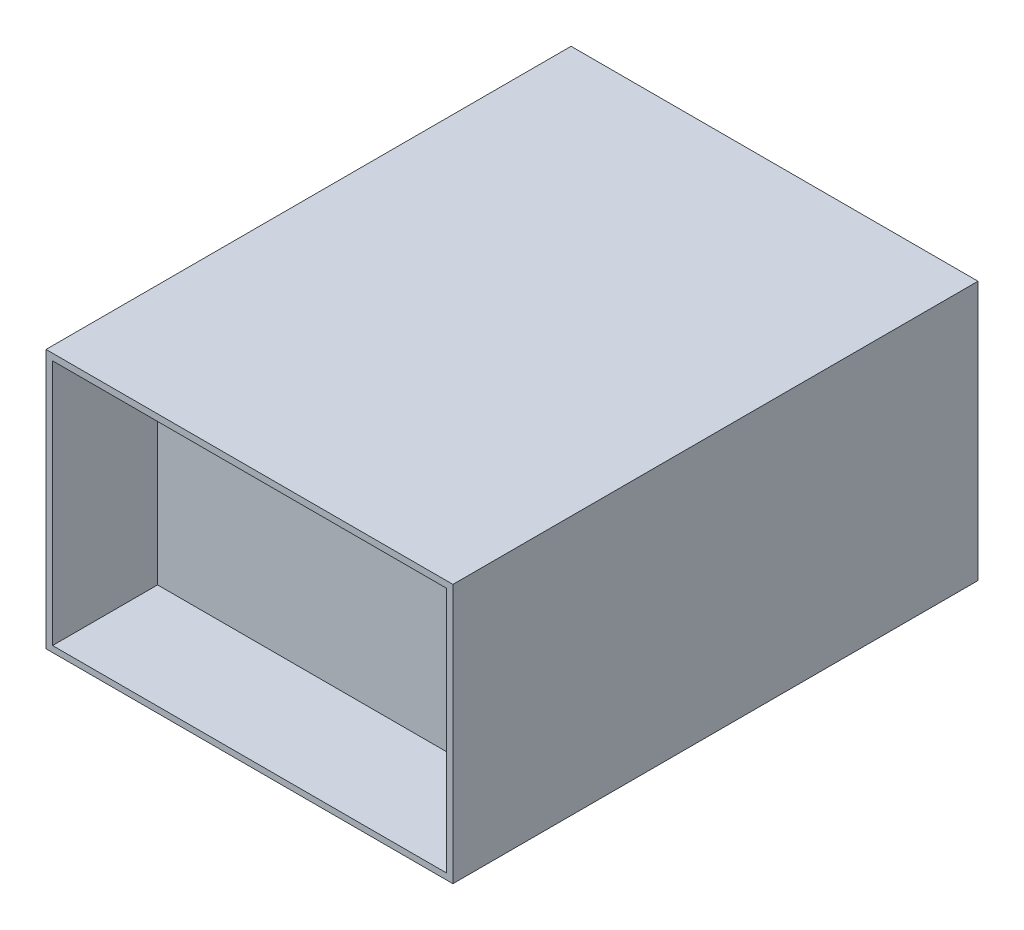
SolidWorks part; units mm, degrees
ref_plane "Front Plane" through (0, 0, 0) normal (0, 0, 1) x (1, 0, 0)
ref_plane "Top Plane" through (0, 0, 0) normal (0, 1, 0) x (1, 0, 0)
ref_plane "Right Plane" through (0, 0, 0) normal (1, 0, 0) x (0, 0, -1)
sketch "Sketch1" plane through (0, 0, 0) normal (0, 0, 1) x (1, 0, 0)
  line L1 (3100, -1975) -> (-3100, -1975)
  line L2 (3100, -1975) -> (3100, 1975)
  line L3 (3100, 1975) -> (-3100, 1975)
  line L4 (-3100, -1975) -> (-3100, 1975)
  line L5 (3100, -1975) -> (-3100, 1975) construction
  line L6 (3100, 1975) -> (-3100, -1975) construction
  point P0 (0, 0)
  dimension "D1" = 6200
  dimension "D2" = 3950
extrude "Boss-Extrude1" add sketch "Sketch1" along normal blind 8000
sketch "Sketch2" plane through (0, 0, 0) normal (0, 0, 1) x (1, 0, 0)
  line L0 (-3100, -1975) -> (3100, -1975) construction
  line L2 (-2500, -1875) -> (2500, -1875)
  line L3 (-2500, -1875) -> (-2500, 1625)
  line L4 (-2500, 1625) -> (2500, 1625)
  line L5 (2500, -1875) -> (2500, 1625)
  line L6 (-3100, 1975) -> (-3100, -1975) construction
  dimension "D1" = 100
  dimension "D2" = 600
  dimension "D3" = 3500
  dimension "D4" = 5000
extrude "Cut-Extrude3" cut sketch "Sketch2" along normal blind 6200
sketch "Sketch4" plane through (0, 0, 0) normal (0, 0, 1) x (1, 0, 0)
  line L0 (2500, -1875) -> (2500, 1625) construction
  line L1 (3000, -1875) -> (2550, -1875)
  line L2 (3000, -1875) -> (3000, 1875)
  line L3 (3000, 1875) -> (2550, 1875)
  line L4 (2550, -1875) -> (2550, 1875)
  line L5 (3100, 1975) -> (-3100, 1975) construction
  line L7 (-3100, 1975) -> (-3100, -1975) construction
  line L8 (-2550, -1882.0855) -> (-3000, -1882.0855)
  line L9 (-2550, -1882.0855) -> (-2550, 1867.9145)
  line L10 (-2550, 1867.9145) -> (-3000, 1867.9145)
  line L11 (-3000, -1882.0855) -> (-3000, 1867.9145)
  point P14 (-2550, 1867.9145)
  dimension "D1" = 450
  dimension "D2" = 50
  dimension "D3" = 3750
  dimension "D4" = 100
  dimension "D5" = 3750
  dimension "D6" = 450
  dimension "D7" = 100
extrude "Cut-Extrude5" cut sketch "Sketch4" along normal blind 6200 contours L10 L11 L8 L9 | L3 L4 L1 L2
sketch "Sketch5" plane through (0, 0, 0) normal (0, 0, -1) x (-1, 0, 0)
  line L0 (-2500, 1625) -> (2500, 1625) construction
  line L1 (-2500, 1875) -> (2500, 1875)
  line L2 (-2500, 1875) -> (-2500, 1675)
  line L3 (-2500, 1675) -> (2500, 1675)
  line L4 (2500, 1875) -> (2500, 1675)
  line L5 (3100, 1975) -> (3100, -1975) construction
  dimension "D1" = 200
  dimension "D2" = 50
  dimension "D3" = 5000
  dimension "D4" = 600
extrude "Cut-Extrude6" cut sketch "Sketch5" against normal blind 8000
sketch "Sketch6" plane through (0, 0, 8000) normal (0, 0, 1) x (1, 0, 0)
  line L1 (-3000, -1882.0855) -> (3000, -1882.0855)
  line L2 (-3000, -1882.0855) -> (-3000, 1875)
  line L3 (-3000, 1875) -> (3000, 1875)
  line L4 (3000, -1882.0855) -> (3000, 1875)
extrude "Cut-Extrude8" cut sketch "Sketch6" against normal blind 1600
